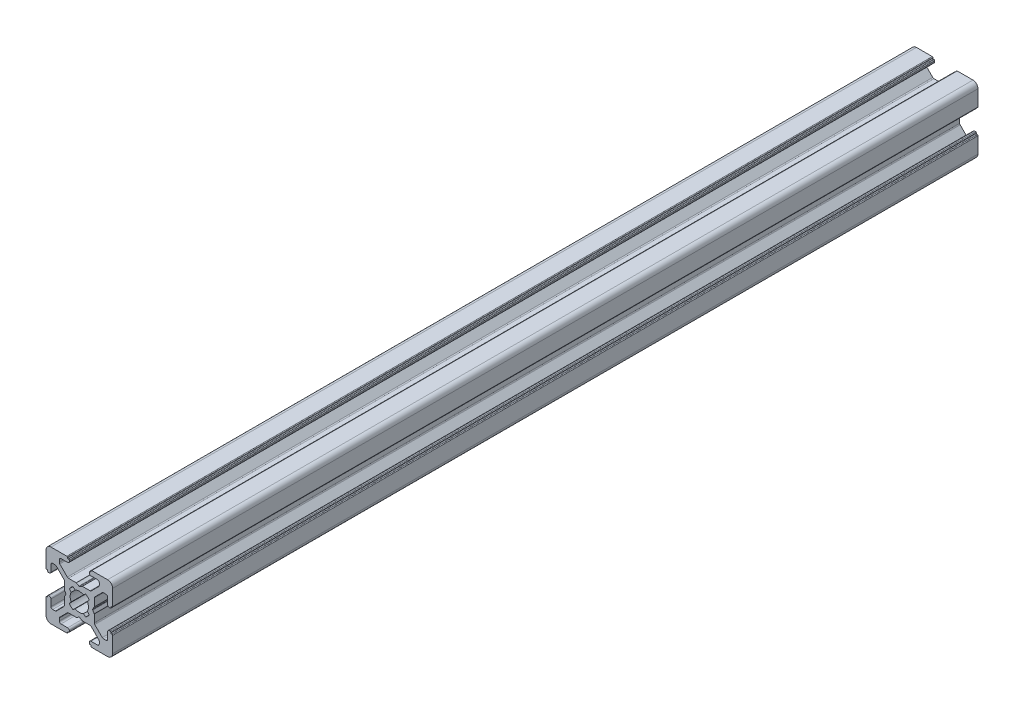
SolidWorks part; units mm, degrees
ref_plane "Front Plane" through (0, 0, 0) normal (0, 0, 1) x (1, 0, 0)
ref_plane "Top Plane" through (0, 0, 0) normal (0, 1, 0) x (1, 0, 0)
ref_plane "Right Plane" through (0, 0, 0) normal (1, 0, 0) x (0, 0, -1)
sketch "Sketch1" plane through (0, 0, 0) normal (0, 0, 1) x (1, 0, 0)
  line L0 (0, 13.3675) -> (0, -10.9159) construction
  line L1 (-12.9725, 0) -> (15.1887, 0) construction
  line L2 (-3.5, 8.5) -> (-5.5, 8.5)
  line L3 (-3.55, 9.7) -> (-3.55, 9.8)
  line L4 (-6, 7.2678) -> (-6, 8)
  line L5 (-7.2678, 6) -> (-8, 6)
  line L6 (-3.75, 10) -> (-8.5, 10)
  line L7 (-9.7, 3.55) -> (-9.8, 3.55)
  line L8 (-9.5, 3.2) -> (-9.5, 3.35)
  line L9 (-9, 3) -> (-9.3, 3)
  line L10 (-4.4732, 0.8536) -> (-4.0381, 0.1)
  line L11 (-4.5, 3.2322) -> (-4.5, 0.9536)
  line L12 (-8.5, 3.5) -> (-8.5, 5.5)
  line L13 (-10, 3.75) -> (-10, 8.5)
  line L14 (-3.5858, 4.6464) -> (-5.8536, 6.9142)
  line L15 (-4.6464, 3.5858) -> (-6.9142, 5.8536)
  line L16 (-3.2, 9.5) -> (-3.35, 9.5)
  line L17 (-3, 9) -> (-3, 9.3)
  line L18 (-0.8536, 4.4732) -> (-0.1, 4.0381)
  line L19 (-3.2322, 4.5) -> (-0.9536, 4.5)
  line L20 (-1.2582, 2.4453) -> (-1.9139, 2.9896)
  line L21 (-2.4453, 1.2582) -> (-2.9922, 1.9099)
  line L22 (3.5, -8.5) -> (5.5, -8.5)
  line L23 (3.55, -9.7) -> (3.55, -9.8)
  line L24 (6, -7.2678) -> (6, -8)
  line L25 (7.2678, -6) -> (8, -6)
  line L26 (3.75, -10) -> (8.5, -10)
  line L27 (9.7, -3.55) -> (9.8, -3.55)
  line L28 (9.5, -3.2) -> (9.5, -3.35)
  line L29 (9, -3) -> (9.3, -3)
  line L30 (4.4732, -0.8536) -> (4.0381, -0.1)
  line L31 (4.5, -3.2322) -> (4.5, -0.9536)
  line L32 (8.5, -3.5) -> (8.5, -5.5)
  line L33 (10, -3.75) -> (10, -8.5)
  line L34 (3.5858, -4.6464) -> (5.8536, -6.9142)
  line L35 (4.6464, -3.5858) -> (6.9142, -5.8536)
  line L36 (3.2, -9.5) -> (3.35, -9.5)
  line L37 (3, -9) -> (3, -9.3)
  line L38 (0.8536, -4.4732) -> (0.1, -4.0381)
  line L39 (3.2322, -4.5) -> (0.9536, -4.5)
  line L40 (1.2582, -2.4453) -> (1.9139, -2.9896)
  line L41 (2.4453, -1.2582) -> (2.9922, -1.9099)
  line L42 (-2.4453, -1.2582) -> (-2.9922, -1.9099)
  line L43 (-1.2582, -2.4453) -> (-1.9139, -2.9896)
  line L44 (-3.2322, -4.5) -> (-0.9536, -4.5)
  line L45 (-0.8536, -4.4732) -> (-0.1, -4.0381)
  line L46 (-3, -9) -> (-3, -9.3)
  line L47 (-3.2, -9.5) -> (-3.35, -9.5)
  line L48 (-4.6464, -3.5858) -> (-6.9142, -5.8536)
  line L49 (-3.5858, -4.6464) -> (-5.8536, -6.9142)
  line L50 (-10, -3.75) -> (-10, -8.5)
  line L51 (-8.5, -3.5) -> (-8.5, -5.5)
  line L52 (-4.5, -3.2322) -> (-4.5, -0.9536)
  line L53 (-4.4732, -0.8536) -> (-4.0381, -0.1)
  line L54 (-9, -3) -> (-9.3, -3)
  line L55 (-9.5, -3.2) -> (-9.5, -3.35)
  line L56 (-9.7, -3.55) -> (-9.8, -3.55)
  line L57 (2.4453, 1.2582) -> (2.9922, 1.9099)
  line L58 (1.2582, 2.4453) -> (1.9139, 2.9896)
  line L59 (3.2322, 4.5) -> (0.9536, 4.5)
  line L60 (0.8536, 4.4732) -> (0.1, 4.0381)
  line L61 (-3.75, -10) -> (-8.5, -10)
  line L62 (-7.2678, -6) -> (-8, -6)
  line L63 (-6, -7.2678) -> (-6, -8)
  line L64 (3, 9) -> (3, 9.3)
  line L65 (3.2, 9.5) -> (3.35, 9.5)
  line L66 (4.6464, 3.5858) -> (6.9142, 5.8536)
  line L67 (3.5858, 4.6464) -> (5.8536, 6.9142)
  line L68 (10, 3.75) -> (10, 8.5)
  line L69 (8.5, 3.5) -> (8.5, 5.5)
  line L70 (4.5, 3.2322) -> (4.5, 0.9536)
  line L71 (4.4732, 0.8536) -> (4.0381, 0.1)
  line L72 (9, 3) -> (9.3, 3)
  line L73 (9.5, 3.2) -> (9.5, 3.35)
  line L74 (9.7, 3.55) -> (9.8, 3.55)
  line L75 (3.75, 10) -> (8.5, 10)
  line L76 (7.2678, 6) -> (8, 6)
  line L77 (6, 7.2678) -> (6, 8)
  line L78 (3.55, 9.7) -> (3.55, 9.8)
  line L79 (3.5, 8.5) -> (5.5, 8.5)
  line L80 (-3.55, -9.7) -> (-3.55, -9.8)
  line L81 (-3.5, -8.5) -> (-5.5, -8.5)
  arc A0 (-10, 8.5) -> (-8.5, 10) centre (-8.5, 8.5) cw
  arc A1 (-8.5, 5.5) -> (-8, 6) centre (-8, 5.5) cw
  arc A2 (-7.2678, 6) -> (-6.9142, 5.8536) centre (-7.2678, 5.5) cw
  arc A3 (-5.8536, 6.9142) -> (-6, 7.2678) centre (-5.5, 7.2678) cw
  arc A4 (-6, 8) -> (-5.5, 8.5) centre (-5.5, 8) cw
  arc A5 (-9.7, 3.55) -> (-9.5, 3.35) centre (-9.7, 3.35) cw
  arc A6 (-9.8, 3.55) -> (-10, 3.75) centre (-9.8, 3.75) cw
  arc A7 (-9.3, 3) -> (-9.5, 3.2) centre (-9.3, 3.2) cw
  arc A8 (-8.5, 3.5) -> (-9, 3) centre (-9, 3.5) cw
  arc A9 (-4.6464, 3.5858) -> (-4.5, 3.2322) centre (-5, 3.2322) cw
  arc A10 (-4.4732, 0.8536) -> (-4.5, 0.9536) centre (-4.3, 0.9536) cw
  arc A11 (-4.0381, 0.1) -> (-4.0381, -0.1) centre (-4.2113, 0) cw
  arc A12 (-3.2, 9.5) -> (-3, 9.3) centre (-3.2, 9.3) cw
  arc A13 (-0.9536, 4.5) -> (-0.8536, 4.4732) centre (-0.9536, 4.3) cw
  arc A14 (-2.9922, 1.9099) -> (-1.9139, 2.9896) centre (0, 0) cw
  arc A15 (-3.2322, 4.5) -> (-3.5858, 4.6464) centre (-3.2322, 5) cw
  arc A16 (-3.75, 10) -> (-3.55, 9.8) centre (-3.75, 9.8) cw
  arc A17 (-3.35, 9.5) -> (-3.55, 9.7) centre (-3.35, 9.7) cw
  arc A18 (2.4453, -1.2582) -> (2.4453, 1.2582) centre (0, 0) ccw
  arc A19 (-3, 9) -> (-3.5, 8.5) centre (-3.5, 9) cw
  arc A20 (-2.4453, -1.2582) -> (-2.4453, 1.2582) centre (0, 0) cw
  arc A21 (10, -8.5) -> (8.5, -10) centre (8.5, -8.5) cw
  arc A22 (8.5, -5.5) -> (8, -6) centre (8, -5.5) cw
  arc A23 (7.2678, -6) -> (6.9142, -5.8536) centre (7.2678, -5.5) cw
  arc A24 (5.8536, -6.9142) -> (6, -7.2678) centre (5.5, -7.2678) cw
  arc A25 (6, -8) -> (5.5, -8.5) centre (5.5, -8) cw
  arc A26 (9.7, -3.55) -> (9.5, -3.35) centre (9.7, -3.35) cw
  arc A27 (9.8, -3.55) -> (10, -3.75) centre (9.8, -3.75) cw
  arc A28 (9.3, -3) -> (9.5, -3.2) centre (9.3, -3.2) cw
  arc A29 (8.5, -3.5) -> (9, -3) centre (9, -3.5) cw
  arc A30 (4.6464, -3.5858) -> (4.5, -3.2322) centre (5, -3.2322) cw
  arc A31 (4.4732, -0.8536) -> (4.5, -0.9536) centre (4.3, -0.9536) cw
  arc A32 (3.2, -9.5) -> (3, -9.3) centre (3.2, -9.3) cw
  arc A33 (-0.1, -4.0381) -> (0.1, -4.0381) centre (0, -4.2113) cw
  arc A34 (0.9536, -4.5) -> (0.8536, -4.4732) centre (0.9536, -4.3) cw
  arc A35 (2.9922, -1.9099) -> (1.9139, -2.9896) centre (0, 0) cw
  arc A36 (1.2582, -2.4453) -> (-1.2582, -2.4453) centre (0, 0) cw
  arc A37 (3.2322, -4.5) -> (3.5858, -4.6464) centre (3.2322, -5) cw
  arc A38 (3.75, -10) -> (3.55, -9.8) centre (3.75, -9.8) cw
  arc A39 (3.35, -9.5) -> (3.55, -9.7) centre (3.35, -9.7) cw
  arc A40 (3, -9) -> (3.5, -8.5) centre (3.5, -9) cw
  arc A41 (-3, -9) -> (-3.5, -8.5) centre (-3.5, -9) ccw
  arc A42 (-3.35, -9.5) -> (-3.55, -9.7) centre (-3.35, -9.7) ccw
  arc A43 (-3.75, -10) -> (-3.55, -9.8) centre (-3.75, -9.8) ccw
  arc A44 (-3.2322, -4.5) -> (-3.5858, -4.6464) centre (-3.2322, -5) ccw
  arc A45 (-2.9922, -1.9099) -> (-1.9139, -2.9896) centre (0, 0) ccw
  arc A46 (-0.9536, -4.5) -> (-0.8536, -4.4732) centre (-0.9536, -4.3) ccw
  arc A47 (-3.2, -9.5) -> (-3, -9.3) centre (-3.2, -9.3) ccw
  arc A48 (-4.4732, -0.8536) -> (-4.5, -0.9536) centre (-4.3, -0.9536) ccw
  arc A49 (3, 9) -> (3.5, 8.5) centre (3.5, 9) ccw
  arc A50 (3.35, 9.5) -> (3.55, 9.7) centre (3.35, 9.7) ccw
  arc A51 (3.75, 10) -> (3.55, 9.8) centre (3.75, 9.8) ccw
  arc A52 (3.2322, 4.5) -> (3.5858, 4.6464) centre (3.2322, 5) ccw
  arc A53 (1.2582, 2.4453) -> (-1.2582, 2.4453) centre (0, 0) ccw
  arc A54 (-4.6464, -3.5858) -> (-4.5, -3.2322) centre (-5, -3.2322) ccw
  arc A55 (-8.5, -3.5) -> (-9, -3) centre (-9, -3.5) ccw
  arc A56 (-9.3, -3) -> (-9.5, -3.2) centre (-9.3, -3.2) ccw
  arc A57 (-9.8, -3.55) -> (-10, -3.75) centre (-9.8, -3.75) ccw
  arc A58 (-9.7, -3.55) -> (-9.5, -3.35) centre (-9.7, -3.35) ccw
  arc A59 (-6, -8) -> (-5.5, -8.5) centre (-5.5, -8) ccw
  arc A60 (2.9922, 1.9099) -> (1.9139, 2.9896) centre (0, 0) ccw
  arc A61 (0.9536, 4.5) -> (0.8536, 4.4732) centre (0.9536, 4.3) ccw
  arc A62 (-0.1, 4.0381) -> (0.1, 4.0381) centre (0, 4.2113) ccw
  arc A63 (-5.8536, -6.9142) -> (-6, -7.2678) centre (-5.5, -7.2678) ccw
  arc A64 (-7.2678, -6) -> (-6.9142, -5.8536) centre (-7.2678, -5.5) ccw
  arc A65 (-8.5, -5.5) -> (-8, -6) centre (-8, -5.5) ccw
  arc A66 (-10, -8.5) -> (-8.5, -10) centre (-8.5, -8.5) ccw
  arc A67 (3.2, 9.5) -> (3, 9.3) centre (3.2, 9.3) ccw
  arc A68 (4.0381, 0.1) -> (4.0381, -0.1) centre (4.2113, 0) ccw
  arc A69 (4.4732, 0.8536) -> (4.5, 0.9536) centre (4.3, 0.9536) ccw
  arc A70 (4.6464, 3.5858) -> (4.5, 3.2322) centre (5, 3.2322) ccw
  arc A71 (8.5, 3.5) -> (9, 3) centre (9, 3.5) ccw
  arc A72 (9.3, 3) -> (9.5, 3.2) centre (9.3, 3.2) ccw
  arc A73 (9.8, 3.55) -> (10, 3.75) centre (9.8, 3.75) ccw
  arc A74 (9.7, 3.55) -> (9.5, 3.35) centre (9.7, 3.35) ccw
  arc A75 (6, 8) -> (5.5, 8.5) centre (5.5, 8) ccw
  arc A76 (5.8536, 6.9142) -> (6, 7.2678) centre (5.5, 7.2678) ccw
  arc A77 (7.2678, 6) -> (6.9142, 5.8536) centre (7.2678, 5.5) ccw
  arc A78 (8.5, 5.5) -> (8, 6) centre (8, 5.5) ccw
  arc A79 (10, 8.5) -> (8.5, 10) centre (8.5, 8.5) ccw
  dimension "D4" = 5.5
  dimension "D1" = 6
  dimension "D2" = 20
  dimension "D3" = 20
  dimension "D5" = 5.5
  dimension "D6" = 10
  dimension "D7" = 6
  dimension "D8" = 6
  dimension "D9" = 6
extrude "Extrude1" add sketch "Sketch1" along normal blind 260
